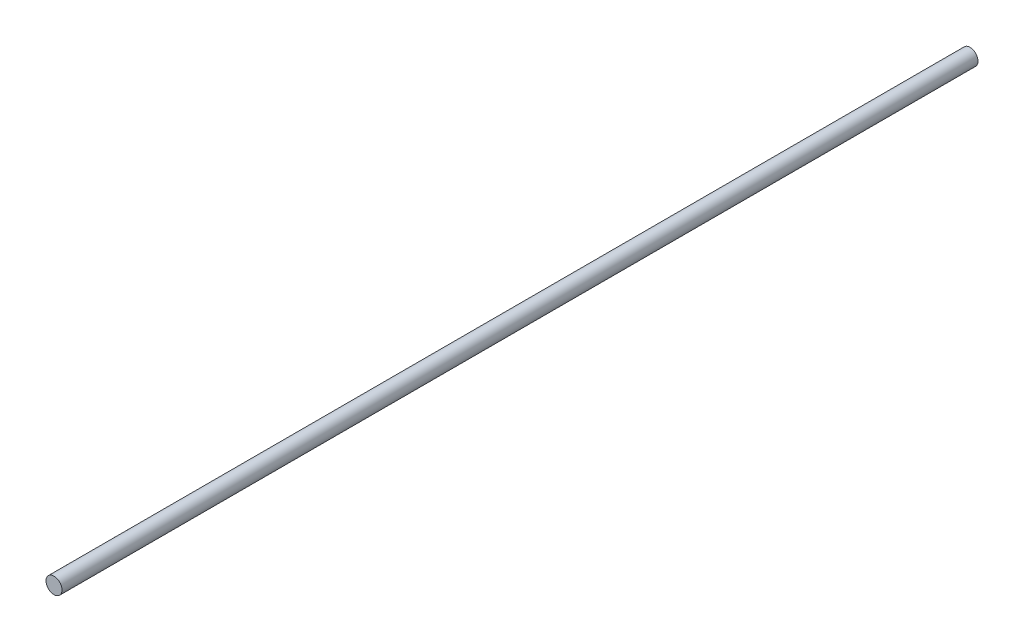
SolidWorks part; units mm, degrees
ref_plane "Front Plane" through (0, 0, 0) normal (0, 0, 1) x (1, 0, 0)
ref_plane "Top Plane" through (0, 0, 0) normal (0, 1, 0) x (1, 0, 0)
ref_plane "Right Plane" through (0, 0, 0) normal (1, 0, 0) x (0, 0, -1)
sketch "Sketch1" plane through (0, 0, 0) normal (0, 0, 1) x (1, 0, 0)
  circle A0 centre (0, 0) radius 4
  dimension "D1" = 8
extrude "Boss-Extrude1" add sketch "Sketch1" along normal blind 457
